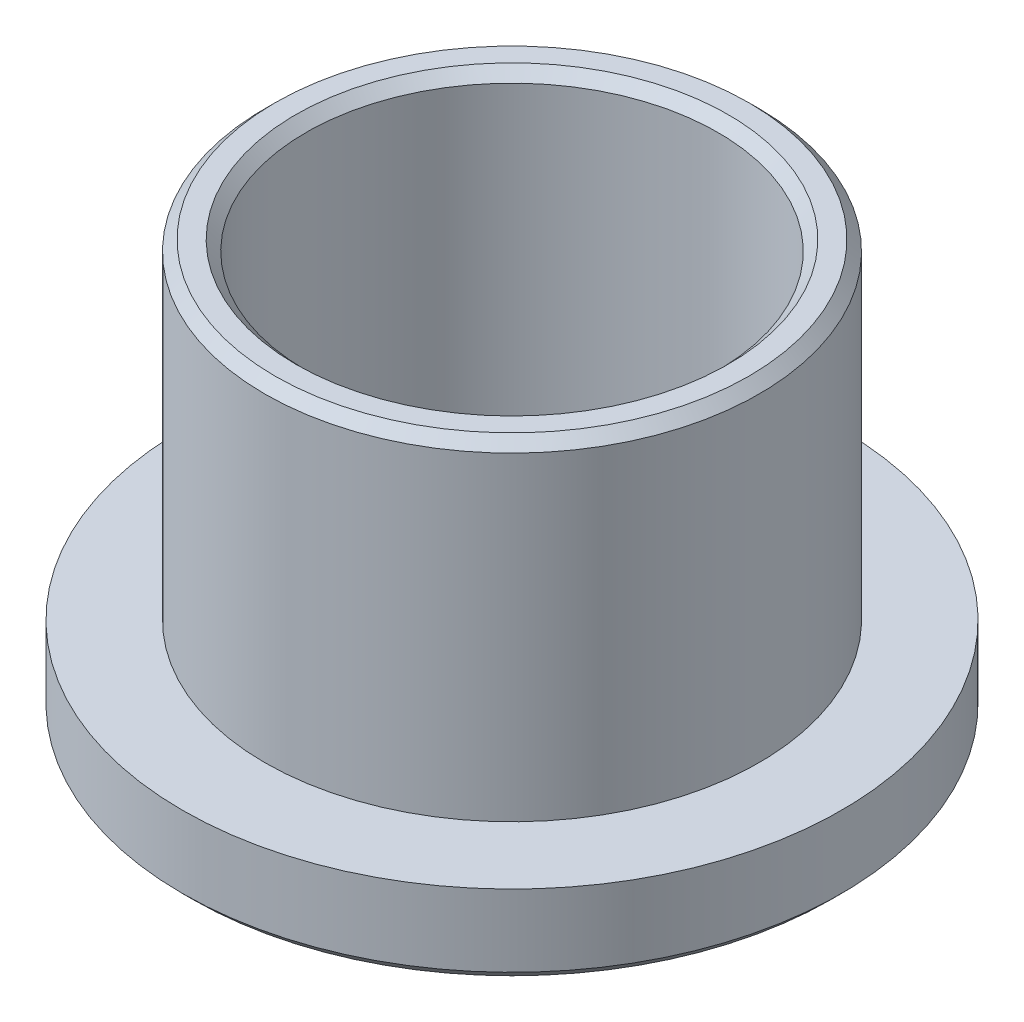
SolidWorks part; units mm, degrees
material "黄铜"
ref_plane "前视基准面" through (0, 0, 0) normal (0, 0, 1) x (1, 0, 0)
ref_plane "上视基准面" through (0, 0, 0) normal (0, 1, 0) x (1, 0, 0)
ref_plane "右视基准面" through (0, 0, 0) normal (1, 0, 0) x (0, 0, -1)
sketch "草图1" plane through (0, 0, 0) normal (0, 1, 0) x (1, 0, 0)
  circle A0 centre (0, 0) radius 8
  circle A1 centre (0, 0) radius 5
extrude "凸台-拉伸1" add sketch "草图1" along normal blind 2
sketch "草图2" plane through (0, 2, 0) normal (0, 1, 0) x (1, 0, 0)
  circle A0 centre (0, 0) radius 5 construction
  circle A1 centre (0, 0) radius 5
  circle A2 centre (0, 0) radius 6
extrude "凸台-拉伸2" add sketch "草图2" along normal blind 8
chamfer "倒角1" distance 0.25 angle 45 4 edges at (0, 0, 5) (0, 0, 8) (0, 10, 5) (0, 10, 6)
